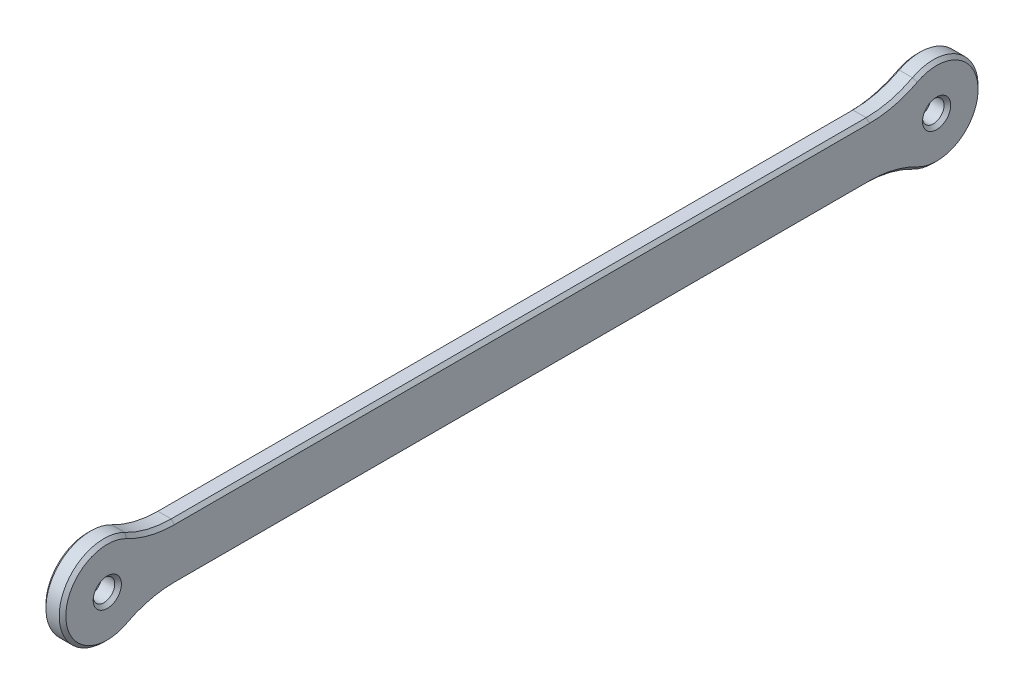
SolidWorks part; units mm, degrees
ref_plane "前视基准面" through (0, 0, 0) normal (0, 0, 1) x (1, 0, 0)
ref_plane "上视基准面" through (0, 0, 0) normal (0, 1, 0) x (1, 0, 0)
ref_plane "右视基准面" through (0, 0, 0) normal (1, 0, 0) x (0, 0, -1)
ref_plane "基准面1" through (-1.5, 0, 0) normal (-1, 0, 0) x (0, -1, 0)
sketch "草图1" plane through (-1.5, 0, 0) normal (-1, 0, 0) x (0, -1, 0)
  line L0 (4.25, -52.3758) -> (4.25, 52.3758)
  line L1 (-4.25, 52.3758) -> (-4.25, -52.3758)
  circle A0 centre (0, -62.5) radius 1.625
  circle A1 centre (0, 62.5) radius 1.625
  arc A2 (-4.25, -52.3758) -> (-5.9741, -59.358) centre (-19.25, -52.3758) cw
  arc A3 (-5.9741, -59.358) -> (5.9741, -59.358) centre (0, -62.5) ccw
  arc A4 (5.9741, -59.358) -> (4.25, -52.3758) centre (19.25, -52.3758) cw
  arc A5 (4.25, 52.3758) -> (5.9741, 59.358) centre (19.25, 52.3758) cw
  arc A6 (5.9741, 59.358) -> (-5.9741, 59.358) centre (0, 62.5) ccw
  arc A7 (-5.9741, 59.358) -> (-4.25, 52.3758) centre (-19.25, 52.3758) cw
extrude "凸台-拉伸1" add sketch "草图1" against normal blind 3
chamfer "倒角1" distance 0.5 angle 45 20 edges at (-1.5, 4.25, 0) (-1.5, 4.6874, 55.9717) (-1.5, 0, 69.25) (-1.5, -4.6874, 55.9717) (-1.5, -4.25, 0) (-1.5, -4.6874, -55.9717) (-1.5, 0, -69.25) (-1.5, 4.6874, -55.9717) (-1.5, 0, -64.125) (-1.5, 0, 60.875) (1.5, 0, -69.25) (1.5, -4.6874, -55.9717) (1.5, -4.25, 0) (1.5, -4.6874, 55.9717) (1.5, 0, 69.25) (1.5, 4.6874, 55.9717) (1.5, 4.25, 0) (1.5, 4.6874, -55.9717) (1.5, 0, -64.125) (1.5, 0, 60.875)
sketch3d "3D草图1"
  line L1 (-1.5, 1.4113, 55.4488) -> (-1.5, 1.4113, -54.6716)
  line L2 (-1.5, 1.4113, 55.4488) -> (-1.5, -1.0282, 55.4488)
  line L3 (-1.5, -1.0282, 55.4488) -> (-1.5, -1.0282, -54.6716)
  line L4 (-1.5, 1.4113, -54.6716) -> (-1.5, -1.0282, -54.6716)
  line L5 (-1.5, 1.4113, 55.4488) -> (-1.5, -1.0282, -54.6716) construction
  line L6 (-1.5, -1.0282, 55.4488) -> (-1.5, 1.4113, -54.6716) construction
  point P0 (-1.5, 0.1915, 0.3886)
extrude "凸台-拉伸2" add sketch "3D草图1" along direction (1, 0, 0) on the side of the normal blind 3
